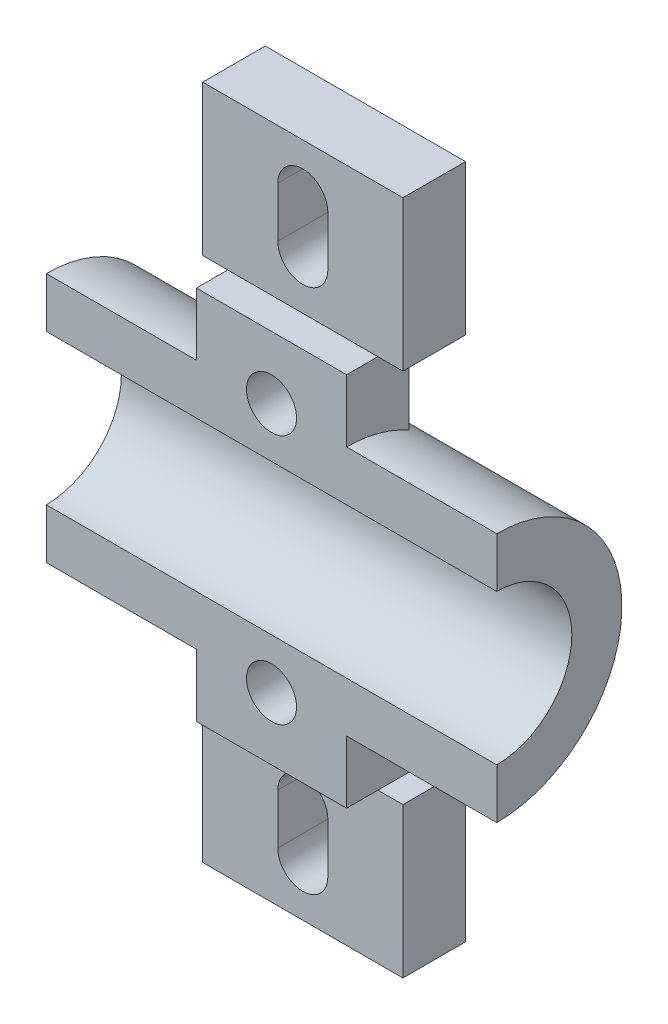
SolidWorks part; units mm, degrees
ref_plane "Front Plane" through (0, 0, 0) normal (1, 0, 0) x (0, 1, 0)
ref_plane "Top Plane" through (0, 0, 0) normal (0, 0, 1) x (0, 1, 0)
ref_plane "Right Plane" through (0, 0, 0) normal (0, 1, 0) x (-1, 0, 0)
sketch "Sketch1" plane through (0, 0, 0) normal (1, 0, 0) x (0, 1, 0)
  line L0 (-50.4845, 0) -> (55.9423, 0) construction
  line L1 (-40, 0) -> (-24, 0)
  line L2 (24, 0) -> (40, 0)
  arc A0 (-40, 0) -> (40, 0) centre (0, 0) ccw
  arc A1 (-24, 0) -> (24, 0) centre (0, 0) ccw
  dimension "D1" = 24
  dimension "D2" = 40
extrude "Boss-Extrude1" add sketch "Sketch1" along normal mid plane 144
ref_plane "Plane1" through (0, 60, 0) normal (0, 1, 0) x (-1, 0, 0)
sketch "Sketch2" plane through (0, 60, 0) normal (0, 1, 0) x (-1, 0, 0)
  line L0 (-24, 0) -> (24, 0)
  line L1 (-72, 0) -> (72, 0) construction
  line L2 (24, 0) -> (24, -20)
  line L3 (24, -20) -> (-24, -20)
  line L4 (-24, 0) -> (-24, -20)
  point P6 (0, 0)
  dimension "D1" = 48
  dimension "D2" = 20
extrude "Boss-Extrude2" add sketch "Sketch2" against normal blind 120
sketch "Sketch4" plane through (24, 0, 0) normal (1, 0, 0) x (0, 1, 0)
  line L0 (-24, 0) -> (24, 0) construction
  circle A0 centre (0, 0) radius 24
extrude "Cut-Extrude1" cut sketch "Sketch4" against normal through all both and the other way through all
sketch "Sketch5" plane through (0, 60, 0) normal (0, 1, 0) x (-1, 0, 0)
  line L0 (-32, -10) -> (32, -10)
  line L1 (-32, -10) -> (-32, -30)
  line L2 (-32, -30) -> (32, -30)
  line L3 (32, -30) -> (32, -10)
  point P3 (0, -10)
extrude "Boss-Extrude3" add sketch "Sketch5" along normal blind 48
mirror "Mirror1" about plane through (0, 0, 0) normal (0, 1, 0) of "Boss-Extrude3"
sketch "Sketch6" plane through (0, 0, 0) normal (0, 0, 1) x (1, 0, 0)
  line L0 (-100.1057, 0) -> (107.9928, 0) construction
  line L1 (0, 92) -> (0, 76) construction
  line L2 (8, 92) -> (8, 76)
  line L3 (-8, 92) -> (-8, 76)
  line L4 (-32, 108) -> (32, 108) construction
  line L5 (0, -92) -> (0, -76) construction
  line L6 (8, -92) -> (8, -76)
  line L7 (-8, -92) -> (-8, -76)
  circle A0 centre (0, 40) radius 8
  arc A1 (8, 92) -> (-8, 92) centre (0, 92) ccw
  arc A2 (-8, 76) -> (8, 76) centre (0, 76) ccw
  arc A3 (8, -92) -> (-8, -92) centre (0, -92) cw
  arc A4 (-8, -76) -> (8, -76) centre (0, -76) cw
  circle A5 centre (0, -40) radius 8
  point P8 (0, 84)
  point P17 (0, -84)
  dimension "D1" = 16
  dimension "D4" = 8
  dimension "D2" = 16
  dimension "D3" = 16
extrude "Cut-Extrude2" cut sketch "Sketch6" against normal through all both and the other way through all
